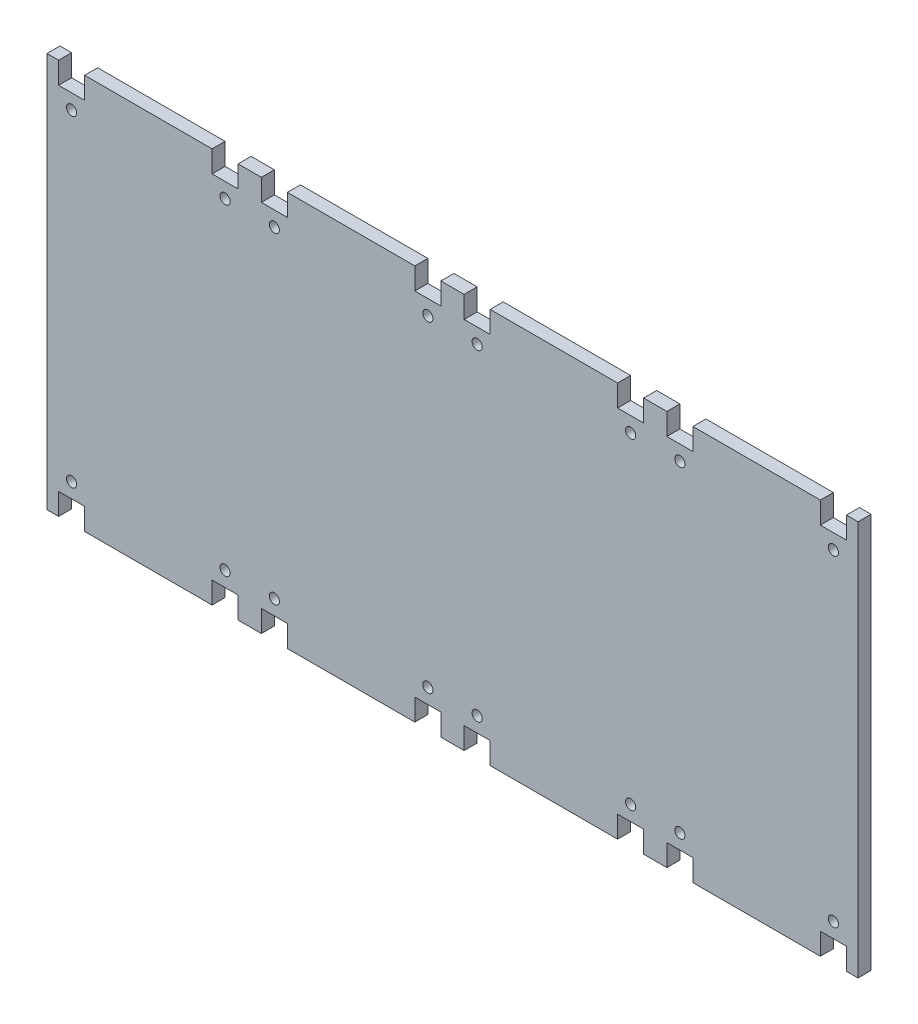
SolidWorks part; units mm, degrees
ref_plane "Front Plane" through (0, 0, 0) normal (0, 0, 1) x (1, 0, 0)
ref_plane "Top Plane" through (0, 0, 0) normal (0, 1, 0) x (1, 0, 0)
ref_plane "Right Plane" through (0, 0, 0) normal (1, 0, 0) x (0, 0, -1)
sketch "Sketch1" plane through (0, 0, 0) normal (0, 0, 1) x (1, 0, 0)
  line L0 (0, 45.5) -> (0, -45.5) construction
  line L1 (-23.35, 45.5) -> (23.35, 45.5)
  line L2 (-23.35, 45.5) -> (-23.35, -45.5)
  line L3 (-23.35, -45.5) -> (23.35, -45.5)
  line L4 (23.35, 45.5) -> (23.35, -45.5)
  line L5 (-23.35, 45.5) -> (23.35, -45.5) construction
  line L6 (-23.35, -45.5) -> (23.35, 45.5) construction
  line L7 (-17.675, 45.5) -> (-17.675, -45.5) construction
  line L8 (-14.675, -45.5) -> (-14.675, 45.5) construction
  line L9 (-20.675, 45.5) -> (-20.675, -45.5) construction
  line L10 (-20.675, -45.5) -> (-17.675, -45.5) construction
  line L11 (-17.675, -45.5) -> (-14.675, -45.5) construction
  line L12 (-23.35, 0) -> (23.35, 0) construction
  line L13 (-20.675, 45.5) -> (-14.675, 45.5)
  line L14 (-20.675, 45.5) -> (-20.675, 40.5)
  line L15 (-20.675, 40.5) -> (-14.675, 40.5)
  line L16 (-14.675, 45.5) -> (-14.675, 40.5)
  line L17 (20.675, 45.5) -> (20.675, -45.5) construction
  line L18 (17.675, 45.5) -> (17.675, -45.5) construction
  line L19 (14.675, -45.5) -> (14.675, 45.5) construction
  line L20 (-23.35, 45.5) -> (-23.35, -45.5)
  line L21 (23.35, 45.5) -> (23.35, -45.5)
  line L22 (14.675, 45.5) -> (14.675, 40.5)
  line L23 (20.675, 40.5) -> (14.675, 40.5)
  line L24 (20.675, 45.5) -> (20.675, 40.5)
  line L25 (20.675, 45.5) -> (14.675, 45.5)
  line L26 (20.675, -45.5) -> (14.675, -45.5)
  line L27 (20.675, -45.5) -> (20.675, -40.5)
  line L28 (20.675, -40.5) -> (14.675, -40.5)
  line L29 (14.675, -45.5) -> (14.675, -40.5)
  line L30 (-14.675, -45.5) -> (-14.675, -40.5)
  line L31 (-20.675, -40.5) -> (-14.675, -40.5)
  line L32 (-20.675, -45.5) -> (-20.675, -40.5)
  line L33 (-20.675, -45.5) -> (-14.675, -45.5)
  line L34 (23.35, 45.5) -> (70.05, 45.5)
  line L35 (23.35, 45.5) -> (23.35, -45.5)
  line L36 (23.35, -45.5) -> (70.05, -45.5)
  line L37 (70.05, 45.5) -> (70.05, -45.5)
  line L38 (26.025, 45.5) -> (32.025, 45.5)
  line L39 (26.025, 45.5) -> (26.025, 40.5)
  line L40 (26.025, 40.5) -> (32.025, 40.5)
  line L41 (32.025, 45.5) -> (32.025, 40.5)
  line L42 (23.35, 45.5) -> (23.35, -45.5)
  line L43 (70.05, 45.5) -> (70.05, -45.5)
  line L44 (61.375, 45.5) -> (61.375, 40.5)
  line L45 (67.375, 40.5) -> (61.375, 40.5)
  line L46 (67.375, 45.5) -> (67.375, 40.5)
  line L47 (67.375, 45.5) -> (61.375, 45.5)
  line L48 (67.375, -45.5) -> (61.375, -45.5)
  line L49 (67.375, -45.5) -> (67.375, -40.5)
  line L50 (67.375, -40.5) -> (61.375, -40.5)
  line L51 (61.375, -45.5) -> (61.375, -40.5)
  line L52 (32.025, -45.5) -> (32.025, -40.5)
  line L53 (26.025, -40.5) -> (32.025, -40.5)
  line L54 (26.025, -45.5) -> (26.025, -40.5)
  line L55 (26.025, -45.5) -> (32.025, -45.5)
  line L56 (46.7, 45.5) -> (46.7, -45.5) construction
  line L57 (23.35, 45.5) -> (70.05, -45.5) construction
  line L58 (23.35, -45.5) -> (70.05, 45.5) construction
  line L59 (29.025, 45.5) -> (29.025, -45.5) construction
  line L60 (32.025, -45.5) -> (32.025, 45.5) construction
  line L61 (26.025, 45.5) -> (26.025, -45.5) construction
  line L62 (26.025, -45.5) -> (29.025, -45.5) construction
  line L63 (29.025, -45.5) -> (32.025, -45.5) construction
  line L64 (23.35, 0) -> (70.05, 0) construction
  line L65 (67.375, 45.5) -> (67.375, -45.5) construction
  line L66 (64.375, 45.5) -> (64.375, -45.5) construction
  line L67 (61.375, -45.5) -> (61.375, 45.5) construction
  line L68 (70.05, 45.5) -> (116.75, 45.5)
  line L69 (70.05, 45.5) -> (70.05, -45.5)
  line L70 (70.05, -45.5) -> (116.75, -45.5)
  line L71 (116.75, 45.5) -> (116.75, -45.5)
  line L72 (72.725, 45.5) -> (78.725, 45.5)
  line L73 (72.725, 45.5) -> (72.725, 40.5)
  line L74 (72.725, 40.5) -> (78.725, 40.5)
  line L75 (78.725, 45.5) -> (78.725, 40.5)
  line L76 (70.05, 45.5) -> (70.05, -45.5)
  line L77 (116.75, 45.5) -> (116.75, -45.5)
  line L78 (108.075, 45.5) -> (108.075, 40.5)
  line L79 (114.075, 40.5) -> (108.075, 40.5)
  line L80 (114.075, 45.5) -> (114.075, 40.5)
  line L81 (114.075, 45.5) -> (108.075, 45.5)
  line L82 (114.075, -45.5) -> (108.075, -45.5)
  line L83 (114.075, -45.5) -> (114.075, -40.5)
  line L84 (114.075, -40.5) -> (108.075, -40.5)
  line L85 (108.075, -45.5) -> (108.075, -40.5)
  line L86 (78.725, -45.5) -> (78.725, -40.5)
  line L87 (72.725, -40.5) -> (78.725, -40.5)
  line L88 (72.725, -45.5) -> (72.725, -40.5)
  line L89 (72.725, -45.5) -> (78.725, -45.5)
  line L90 (93.4, 45.5) -> (93.4, -45.5) construction
  line L91 (70.05, 45.5) -> (116.75, -45.5) construction
  line L92 (70.05, -45.5) -> (116.75, 45.5) construction
  line L93 (75.725, 45.5) -> (75.725, -45.5) construction
  line L94 (78.725, -45.5) -> (78.725, 45.5) construction
  line L95 (72.725, 45.5) -> (72.725, -45.5) construction
  line L96 (72.725, -45.5) -> (75.725, -45.5) construction
  line L97 (75.725, -45.5) -> (78.725, -45.5) construction
  line L98 (70.05, 0) -> (116.75, 0) construction
  line L99 (114.075, 45.5) -> (114.075, -45.5) construction
  line L100 (111.075, 45.5) -> (111.075, -45.5) construction
  line L101 (108.075, -45.5) -> (108.075, 45.5) construction
  line L102 (116.75, 45.5) -> (163.45, 45.5)
  line L103 (116.75, 45.5) -> (116.75, -45.5)
  line L104 (116.75, -45.5) -> (163.45, -45.5)
  line L105 (163.45, 45.5) -> (163.45, -45.5)
  line L106 (119.425, 45.5) -> (125.425, 45.5)
  line L107 (119.425, 45.5) -> (119.425, 40.5)
  line L108 (119.425, 40.5) -> (125.425, 40.5)
  line L109 (125.425, 45.5) -> (125.425, 40.5)
  line L110 (116.75, 45.5) -> (116.75, -45.5)
  line L111 (163.45, 45.5) -> (163.45, -45.5)
  line L112 (154.775, 45.5) -> (154.775, 40.5)
  line L113 (160.775, 40.5) -> (154.775, 40.5)
  line L114 (160.775, 45.5) -> (160.775, 40.5)
  line L115 (160.775, 45.5) -> (154.775, 45.5)
  line L116 (160.775, -45.5) -> (154.775, -45.5)
  line L117 (160.775, -45.5) -> (160.775, -40.5)
  line L118 (160.775, -40.5) -> (154.775, -40.5)
  line L119 (154.775, -45.5) -> (154.775, -40.5)
  line L120 (125.425, -45.5) -> (125.425, -40.5)
  line L121 (119.425, -40.5) -> (125.425, -40.5)
  line L122 (119.425, -45.5) -> (119.425, -40.5)
  line L123 (119.425, -45.5) -> (125.425, -45.5)
  line L124 (140.1, 45.5) -> (140.1, -45.5) construction
  line L125 (116.75, 45.5) -> (163.45, -45.5) construction
  line L126 (116.75, -45.5) -> (163.45, 45.5) construction
  line L127 (122.425, 45.5) -> (122.425, -45.5) construction
  line L128 (125.425, -45.5) -> (125.425, 45.5) construction
  line L129 (119.425, 45.5) -> (119.425, -45.5) construction
  line L130 (119.425, -45.5) -> (122.425, -45.5) construction
  line L131 (122.425, -45.5) -> (125.425, -45.5) construction
  line L132 (116.75, 0) -> (163.45, 0) construction
  line L133 (160.775, 45.5) -> (160.775, -45.5) construction
  line L134 (157.775, 45.5) -> (157.775, -45.5) construction
  line L135 (154.775, -45.5) -> (154.775, 45.5) construction
  circle A0 centre (-17.675, 37.05) radius 1.1688
  circle A1 centre (17.675, 37.05) radius 1.1688
  circle A2 centre (17.675, -37.05) radius 1.1688
  circle A3 centre (-17.675, -37.05) radius 1.1688
  circle A4 centre (29.025, 37.05) radius 1.1688
  circle A5 centre (64.375, 37.05) radius 1.1688
  circle A6 centre (64.375, -37.05) radius 1.1688
  circle A7 centre (29.025, -37.05) radius 1.1688
  circle A8 centre (75.725, 37.05) radius 1.1688
  circle A9 centre (111.075, 37.05) radius 1.1688
  circle A10 centre (111.075, -37.05) radius 1.1688
  circle A11 centre (75.725, -37.05) radius 1.1688
  circle A12 centre (122.425, 37.05) radius 1.1688
  circle A13 centre (157.775, 37.05) radius 1.1688
  circle A14 centre (157.775, -37.05) radius 1.1688
  circle A15 centre (122.425, -37.05) radius 1.1688
  point P0 (0, 0)
  point P40 (46.7, 0)
  point P77 (93.4, 0)
  point P114 (140.1, 0)
  dimension "D1" = 46.7
  dimension "D2" = 91
  dimension "D3" = 6
  dimension "D4" = 5
  dimension "D5" = 8.45
  dimension "D6" = 35.35
  dimension "D7" = 4
extrude "Boss-Extrude1" add sketch "Sketch1" along normal blind 3 contours L36 L54 L53 L52 L51 L50 L49 L37 L34 L46 L45 L44 L41 L40 L39 L4 A5 A4 A6 A7 | L3 L32 L31 L30 L29 L28 L27 L4 L1 L24 L23 L22 L16 L15 L14 L2 A1 A0 A2 A3 | L70 L88 L87 L86 L85 L84 L83 L71 L68 L80 L79 L78 L75 L74 L73 L37 A9 A8 A10 A11 | L104 L122 L121 L120 L119 L118 L117 L105 L102 L114 L113 L112 L109 L108 L107 L71 A13 A12 A14 A15
